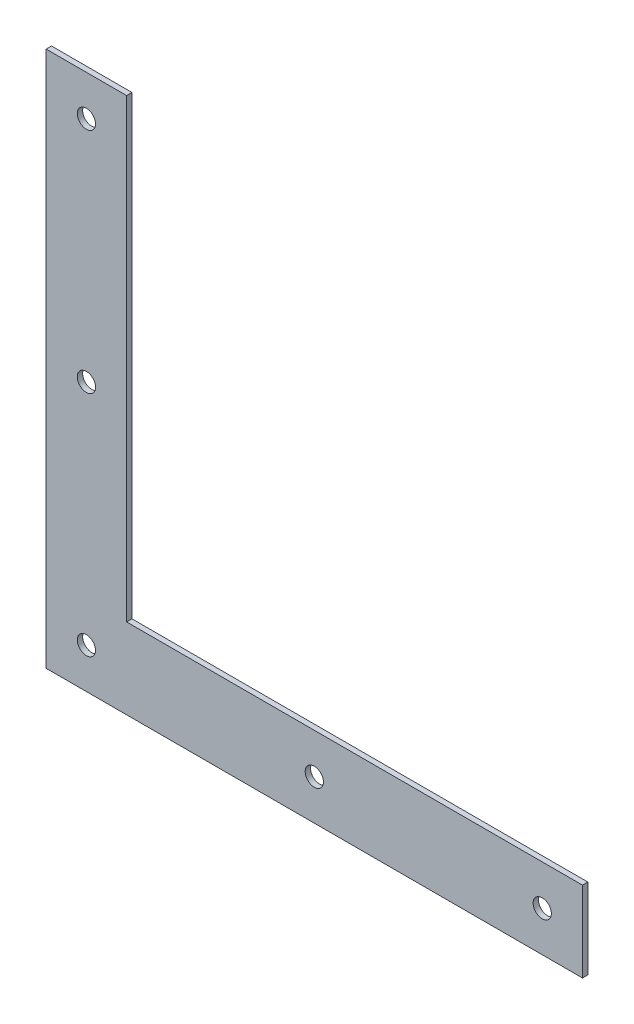
SolidWorks part; units mm, degrees
ref_plane "Front Plane" through (0, 0, 0) normal (0, 0, 1) x (1, 0, 0)
ref_plane "Top Plane" through (0, 0, 0) normal (0, 1, 0) x (1, 0, 0)
ref_plane "Right Plane" through (0, 0, 0) normal (1, 0, 0) x (0, 0, -1)
sketch "Sketch1" plane through (0, 0, 0) normal (0, 0, 1) x (1, 0, 0)
  line L0 (0, 0) -> (0, 100)
  line L1 (0, 100) -> (15, 100)
  line L2 (15, 100) -> (15, 15)
  line L3 (15, 15) -> (100, 15)
  line L4 (100, 15) -> (100, 0)
  line L5 (100, 0) -> (0, 0)
  dimension "D1" = 15
  dimension "D2" = 15
  dimension "D3" = 100
  dimension "D4" = 100
extrude "Boss-Extrude1" add sketch "Sketch1" along normal blind 1
hole_wizard "M3 Clearance Hole1" positions "Sketch2" profile "Sketch3" hole size "M3" standard "ANSI Metric" end condition through all
sketch "Sketch2" plane through (0, 0, 0) normal (0, 0, -1) x (-1, 0, 0)
  line L0 (-100, 0) -> (-100, 15) construction
  line L1 (-15, 100) -> (0, 100) construction
  line L2 (0, 100) -> (0, 0) construction
  line L3 (0, 0) -> (-100, 0) construction
  point P0 (-92.5, 7.5)
  point P2 (-7.5, 7.5)
  point P4 (-7.5, 92.5)
  point P6 (-7.5, 50)
  point P8 (-50, 7.5)
  point P13 (-100, 7.5)
  point P17 (-7.5, 100)
  point P21 (0, 50)
  point P25 (-50, 0)
  dimension "D1" = 7.5
  dimension "D2" = 7.5
sketch "Sketch3" plane through (92.5, 7.5, 0) normal (1, 0, 0) x (0, 1, 0)
  line L0 (0, 0) -> (0, 1)
  line L1 (0, 1) -> (1.7, 1)
  line L2 (1.7, 1) -> (1.7, 0)
  line L5 (1.7, 0) -> (0, 0)
  line L11 (0, -6.35) -> (0, 107.95) construction
  dimension "Thru Hole Dia." = 3.4
  dimension "Thru Hole Depth" = 1
